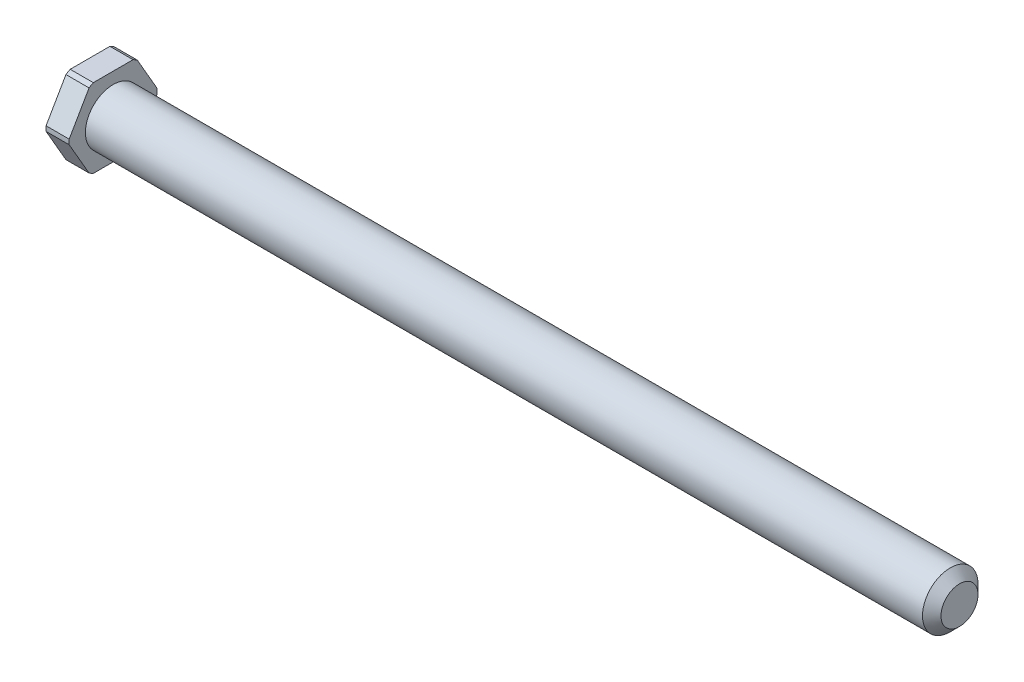
SolidWorks part; units mm, degrees
material "AISI 1020"
ref_plane "Alzado" through (0, 0, 0) normal (0, 0, 1) x (1, 0, 0)
ref_plane "Planta" through (0, 0, 0) normal (0, 1, 0) x (1, 0, 0)
ref_plane "Vista lateral" through (0, 0, 0) normal (1, 0, 0) x (0, 0, -1)
sketch "Croquis1" plane through (0, 0, 0) normal (0, 0, 1) x (1, 0, 0)
  line L0 (0, 0) -> (188, 0)
  line L15 (188, 0) -> (188, 6)
  line L21 (0, 9.525) -> (0, 0)
  line L22 (0, 9.525) -> (5, 9.525)
  line L23 (5, 9.525) -> (5, 6)
  line L24 (5, 6) -> (188, 6)
  dimension "D1" = 9.525
  dimension "D2" = 183
  dimension "D3" = 6
  dimension "D5" = 5
revolve "Revolución1" add sketch "Croquis1" angle 360 about L0
chamfer "Chaflán1" distance 2 angle 45 1 edges at (188, 0, 6)
sketch "Croquis2" plane through (0, 0, 0) normal (-1, 0, 0) x (0, 0, 1)
  line L3 (4.9075, 8.5) -> (-4.9075, 8.5)
  line L4 (-4.9075, 8.5) -> (-9.815, 0)
  line L5 (-9.815, 0) -> (-4.9075, -8.5)
  line L6 (-4.9075, -8.5) -> (4.9075, -8.5)
  line L7 (4.9075, -8.5) -> (9.815, 0)
  line L8 (9.815, 0) -> (4.9075, 8.5)
  circle A3 centre (0, 0) radius 8.5 construction
  circle A4 centre (0, 0) radius 9.525 construction
  circle A5 centre (0, 0) radius 9.525
  circle M4 centre (0, 0) radius 9.525
  dimension "D1" = 17
extrude "Cortar-Extruir1" cut sketch "Croquis2" against normal up to next contours L3 M4 | L4 M4 | L5 M4 | L6 M4 | L7 M4 | L8 M4
